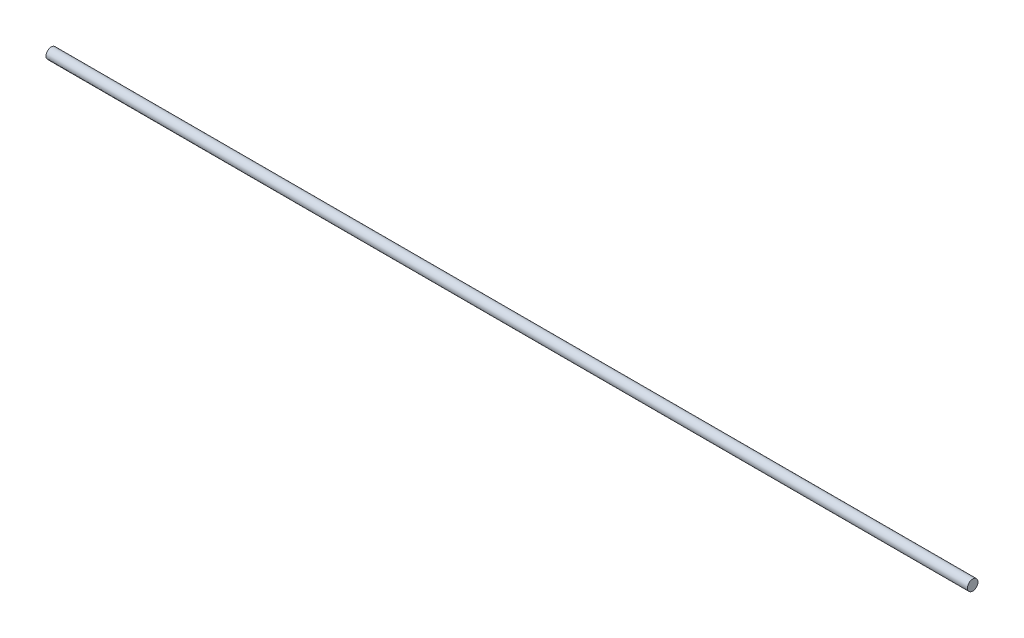
SolidWorks part; units mm, degrees
ref_plane "Alzado" through (0, 0, 0) normal (0, 0, 1) x (1, 0, 0)
ref_plane "Planta" through (0, 0, 0) normal (0, 1, 0) x (1, 0, 0)
ref_plane "Vista lateral" through (0, 0, 0) normal (1, 0, 0) x (0, 0, -1)
sketch "Croquis1" plane through (0, 0, 0) normal (1, 0, 0) x (0, 0, -1)
  circle A0 centre (0, 0) radius 4
  dimension "D1" = 8
extrude "Saliente-Extruir1" add sketch "Croquis1" along normal blind 700
